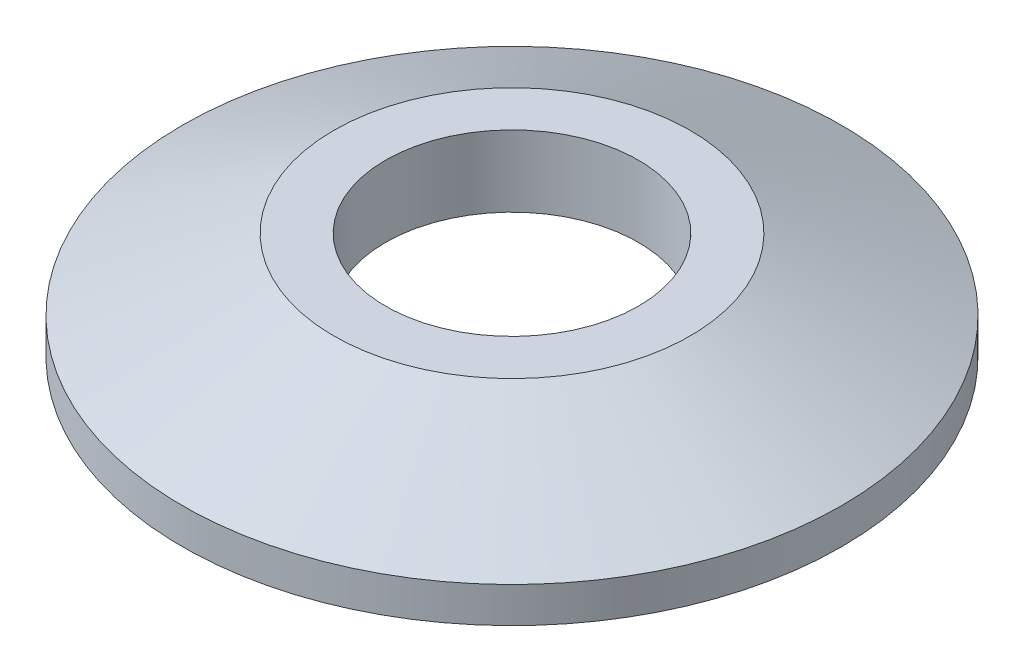
SolidWorks part; units mm, degrees
material "Plain Carbon Steel"
ref_plane "Front Plane" through (0, 0, 0) normal (0, 0, 1) x (1, 0, 0)
ref_plane "Top Plane" through (0, 0, 0) normal (0, 1, 0) x (1, 0, 0)
ref_plane "Right Plane" through (0, 0, 0) normal (1, 0, 0) x (0, 0, -1)
sketch "Sketch1" plane through (0, 0, 0) normal (0, 0, 1) x (1, 0, 0)
  line L0 (-18.5, 0) -> (-18.5, 2)
  line L1 (-18.5, 2) -> (-10, 6)
  line L2 (-10, 6) -> (-7.1, 6)
  line L3 (-7.1, 6) -> (-7.1, 2)
  line L4 (-7.1, 2) -> (-10, 2)
  line L5 (-10, 2) -> (-10, 0)
  line L6 (-10, 0) -> (-18.5, 0)
  line L7 (0, 22.2676) -> (0, -14.7324) construction
  dimension "D1" = 14.2
  dimension "D2" = 20
  dimension "D3" = 20
  dimension "D4" = 37
  dimension "D5" = 2
  dimension "D6" = 6
revolve "Revolve1" add sketch "Sketch1" angle 360 about L7
